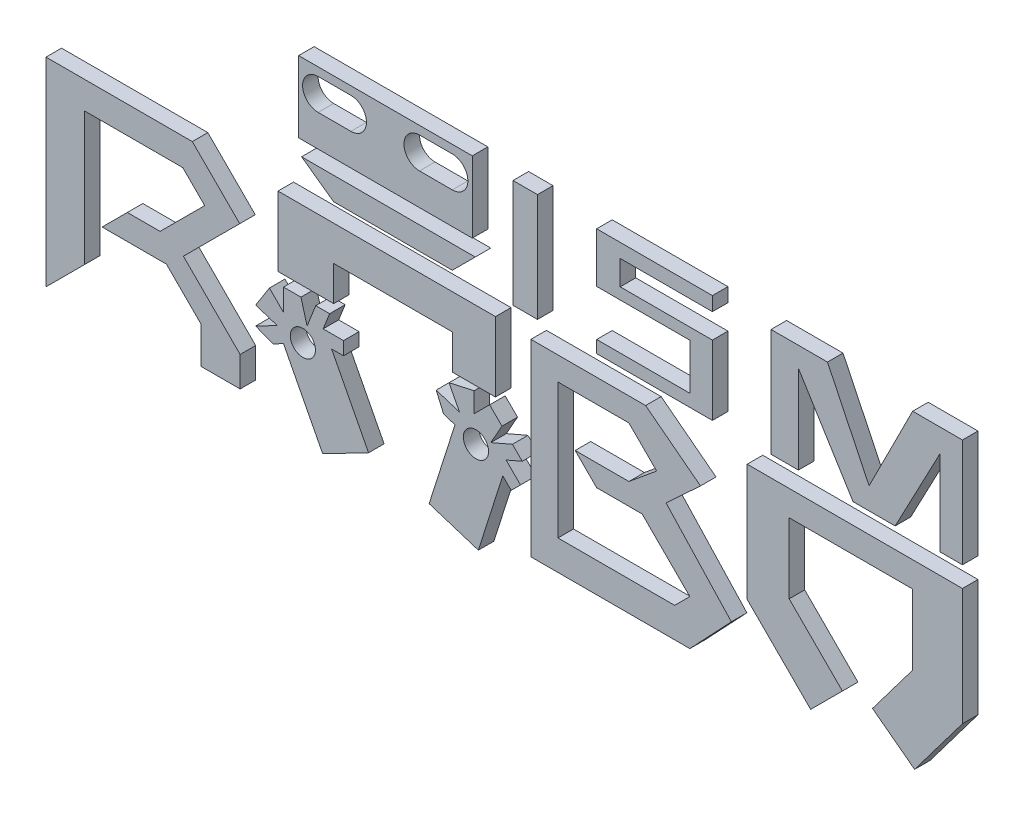
SolidWorks part; units mm, degrees
ref_plane "Front Plane" through (0, 0, 0) normal (0, 0, 1) x (1, 0, 0)
ref_plane "Top Plane" through (0, 0, 0) normal (0, 1, 0) x (1, 0, 0)
ref_plane "Right Plane" through (0, 0, 0) normal (1, 0, 0) x (0, 0, -1)
sketch "Sketch1" plane through (0, 0, 0) normal (0, 0, 1) x (1, 0, 0)
  line L0 (-187.765, 24.8798) -> (-187.765, -40.178)
  line L1 (-187.765, -40.178) -> (-175.1759, -27.5889)
  line L2 (-175.1759, -27.5889) -> (-175.1759, 15.9373)
  line L3 (-175.1759, 15.9373) -> (-143.0335, 15.9373)
  line L4 (-187.765, 24.8798) -> (-139.9227, 24.8798)
  line L5 (-139.9227, 24.8798) -> (-124.4177, 9.3749)
  line L6 (-143.0335, 15.9373) -> (-135.8684, 8.7722)
  line L7 (-135.8684, 8.7722) -> (-150.4664, -5.8258)
  line L8 (-150.4664, -5.8258) -> (-161.1806, -5.8258)
  line L9 (-161.1806, -5.8258) -> (-169.417, -14.0623)
  line L10 (-169.417, -14.0623) -> (-148.3906, -14.0623)
  line L11 (-148.3906, -14.0623) -> (-137.1407, -25.3121)
  line L12 (-137.1407, -25.3121) -> (-137.1407, -37.3655)
  line L13 (-124.4177, 9.3749) -> (-142.8326, -9.04)
  line L14 (-142.8326, -9.04) -> (-124.2838, -27.5889)
  line L15 (-124.2838, -27.5889) -> (-124.2838, -37.3655)
  line L16 (-124.2838, -37.3655) -> (-137.1407, -37.3655)
  line L17 (-105.4731, 24.8798) -> (-48.6883, 24.8798)
  line L18 (-105.4731, 24.8798) -> (-111.9016, 24.8798)
  line L33 (-40.7899, 24.8798) -> (-45.3328, 24.8798)
  line L34 (-45.3328, 24.8798) -> (-48.6883, 24.8798)
  line L35 (-29.196, 24.2407) -> (-29.196, -37.3655)
  line L36 (-86.2487, 10.4463) -> (-62.1419, 10.4463)
  line L37 (-86.2487, 10.4463) -> (-86.2487, -10.3123)
  line L38 (-86.2487, -10.3123) -> (-62.1419, -10.3123)
  line L39 (-62.1419, 10.4463) -> (-62.1419, -10.3123)
  line L44 (-29.196, -37.3655) -> (22.7675, -37.3655)
  line L45 (-29.196, 24.2407) -> (8.3034, 24.2407)
  line L46 (8.3034, 24.2407) -> (26.2496, 10.4463)
  line L47 (26.2496, 10.4463) -> (14.9998, 0)
  line L48 (14.9998, 0) -> (36.3407, -22.9825)
  line L49 (22.7675, -37.3655) -> (36.3407, -22.9825)
  line L50 (-111.9016, 24.8798) -> (-111.9016, 2.1001)
  line L51 (-20.3568, 16.5764) -> (2.8429, 16.5764)
  line L52 (2.8429, 16.5764) -> (11.9195, 7.4999)
  line L54 (7.1651, -7.0311) -> (22.7675, -22.6336)
  line L55 (22.7675, -22.6336) -> (17.8122, -27.5889)
  line L57 (-20.3568, -27.5889) -> (-20.3568, 16.5764)
  line L58 (-14.7319, 0) -> (2.8429, 0)
  line L59 (-14.7319, 0) -> (-7.7008, -7.0311)
  line L60 (-7.7008, -7.0311) -> (7.1651, -7.0311)
  line L61 (17.8122, -27.5889) -> (-20.3568, -27.5889)
  line L62 (41.5172, 24.2407) -> (41.5172, -14.0623)
  line L63 (41.5172, -14.0623) -> (62.2758, -34.8209)
  line L64 (72.6551, -24.4416) -> (62.2758, -34.8209)
  line L65 (72.6551, -24.4416) -> (55.2447, -7.0311)
  line L66 (55.2447, -7.0311) -> (55.2447, 15.9373)
  line L67 (55.2447, 15.9373) -> (95.6235, 15.9373)
  line L68 (95.6235, 15.9373) -> (95.6235, -7.0311)
  line L69 (95.6235, -7.0311) -> (82.4987, -24.4416)
  line L70 (82.4987, -24.4416) -> (96.2672, -34.8209)
  line L71 (96.2672, -34.8209) -> (111.916, -14.0623)
  line L72 (111.916, -14.0623) -> (111.916, 24.2407)
  line L73 (111.916, 24.2407) -> (41.5172, 24.2407)
  line L74 (-93.695, 30.937) -> (-54.9099, 30.937)
  line L75 (-54.9099, 30.937) -> (-47.41, 38.4369)
  line L76 (-47.41, 38.4369) -> (-104.1948, 38.4369)
  line L77 (-104.1948, 38.4369) -> (-93.695, 30.937)
  line L78 (-98.7817, 58.7937) -> (-88.0676, 58.7937) construction
  line L79 (-105.1597, 43.312) -> (-48.3748, 43.312)
  line L80 (-105.1597, 43.312) -> (-105.1597, 66.6152)
  line L81 (-105.1597, 66.6152) -> (-48.3748, 66.6152)
  line L82 (-48.3748, 43.312) -> (-48.3748, 66.6152)
  line L85 (-65.624, 58.7937) -> (-54.9099, 58.7937) construction
  line L86 (-65.624, 63.8829) -> (-54.9099, 63.8829)
  line L87 (-65.624, 53.7045) -> (-54.9099, 53.7045)
  line L88 (104.6063, 30.937) -> (111.916, 30.937)
  line L91 (-63.8829, 59.0616) -> (-57.1866, 59.0616) construction
  line L92 (-63.8829, 61.7401) -> (-57.1866, 61.7401)
  line L93 (-63.8829, 56.3831) -> (-57.1866, 56.3831)
  line L94 (111.916, 30.937) -> (111.916, 66.2936)
  line L95 (111.916, 66.2936) -> (104.6063, 66.2936)
  line L96 (104.6063, 66.2936) -> (95.6235, 66.2936)
  line L97 (104.6063, 30.937) -> (104.6063, 58.7937)
  line L98 (104.6063, 58.7937) -> (89.9058, 30.937)
  line L99 (89.9058, 30.937) -> (76.1379, 30.937)
  line L100 (76.1379, 30.937) -> (58.2678, 59.7833)
  line L101 (58.2678, 59.7833) -> (58.2678, 30.937)
  line L102 (58.2678, 30.937) -> (49.3197, 30.937)
  line L103 (49.3197, 30.937) -> (49.3197, 66.2936)
  line L104 (49.3197, 66.2936) -> (67.7728, 66.2936)
  line L105 (67.7728, 66.2936) -> (81.3854, 38.0643)
  line L106 (81.3854, 38.0643) -> (95.6235, 66.2936)
  line L107 (-35.0483, 66.2936) -> (-35.0483, 30.937)
  line L108 (-35.0483, 30.937) -> (-27.0589, 30.937)
  line L109 (-27.0589, 30.937) -> (-27.0589, 66.2936)
  line L110 (-27.0589, 66.2936) -> (-35.0483, 66.2936)
  line L111 (30.1451, 66.2936) -> (-7.7008, 66.2936)
  line L112 (-7.7008, 49.9688) -> (-7.7008, 66.2936)
  line L113 (-7.7008, 49.9688) -> (22.7675, 49.9688)
  line L114 (22.7675, 49.9688) -> (22.7675, 34.9488)
  line L115 (22.7675, 34.9488) -> (-7.7008, 34.9488)
  line L116 (-7.7008, 34.9488) -> (-7.7008, 30.937)
  line L117 (-7.7008, 30.937) -> (30.1451, 30.937)
  line L118 (30.1451, 30.937) -> (30.1451, 53.7045)
  line L119 (30.1451, 53.7045) -> (0, 53.7045)
  line L120 (30.1451, 66.2936) -> (30.1451, 61.7401)
  line L121 (30.1451, 61.7401) -> (0, 61.7401)
  line L122 (0, 61.7401) -> (0, 53.7045)
  line L147 (-98.7817, 63.8829) -> (-88.0676, 63.8829)
  line L150 (-98.7817, 53.7045) -> (-88.0676, 53.7045)
  line L151 (-97.0407, 59.0616) -> (-90.3444, 59.0616) construction
  line L152 (-97.0407, 61.7401) -> (-90.3444, 61.7401)
  line L153 (-97.0407, 56.3831) -> (-90.3444, 56.3831)
  line L154 (-111.9016, 2.1001) -> (-93.695, 2.1001)
  line L155 (11.9195, 7.4999) -> (2.8429, 0)
  line L156 (-93.695, 2.1001) -> (-93.695, 13.49)
  line L157 (-93.695, 13.49) -> (-54.9099, 13.49)
  line L158 (-54.9099, 13.49) -> (-54.9099, 2.1001)
  line L159 (-54.9099, 2.1001) -> (-40.7899, 2.1001)
  line L160 (-40.7899, 2.1001) -> (-40.7899, 24.8798)
  line L161 (-37.3089, -13.9973) -> (-32.6029, -18.7034)
  line L162 (-38.6583, -5.0798) -> (-42.3284, -11.5723)
  line L163 (-57.7515, -11.1973) -> (-54.0286, -12.3819)
  line L164 (-47.7737, 0.3894) -> (-47.7737, -6.127)
  line L165 (-62.4816, -38.9483) -> (-48.8511, -43.2853)
  line L166 (-38.4086, -19.0026) -> (-46.3846, -44.0701)
  line L167 (-52.5593, -8.0423) -> (-60.1659, -5.622)
  line L168 (-35.2369, -8.5013) -> (-32.0279, -11.7103)
  line L169 (-46.3846, -44.0701) -> (-48.8511, -43.2853)
  line L170 (-32.0279, -11.7103) -> (-37.3089, -13.9973)
  line L171 (-42.6924, -1.0457) -> (-38.6583, -5.0798)
  line L172 (-55.9775, -1.4337) -> (-47.7737, 0.3894)
  line L173 (-60.1659, -5.622) -> (-57.7515, -11.1973)
  line L174 (-55.9775, -1.4337) -> (-52.5593, -8.0423)
  line L175 (-38.4086, -19.0026) -> (-35.6554, -21.7559)
  line L176 (-47.7737, -6.127) -> (-42.6924, -1.0457)
  line L177 (-32.6029, -18.7034) -> (-35.6554, -21.7559)
  line L184 (-54.0286, -12.3819) -> (-62.4816, -38.9483)
  line L185 (-35.2369, -8.5013) -> (-42.3284, -11.5723)
  line L188 (-114.7057, -3.9857) -> (-110.0979, -8.5934)
  line L189 (-110.0979, -8.5934) -> (-110.0979, -1.4075)
  line L190 (-119.2175, -11.0757) -> (-112.1275, -13.3317)
  line L191 (-112.1275, -13.3317) -> (-119.2175, -16.999)
  line L192 (-104.3928, -1.4075) -> (-102.3971, -8.5934)
  line L193 (-94.3714, -11.0757) -> (-82.2859, -34.441)
  line L194 (-99.5542, -1.4075) -> (-102.3971, -8.5934)
  line L195 (-94.3714, -11.0757) -> (-90.4777, -11.0757)
  line L196 (-95.0159, -1.4075) -> (-97.1331, -6.7589)
  line L197 (-97.1331, -6.7589) -> (-90.4777, -6.7589)
  line L198 (-119.2175, -11.0757) -> (-114.7057, -3.9857)
  line L199 (-110.0979, -1.4075) -> (-104.3928, -1.4075)
  line L200 (-99.5542, -1.4075) -> (-95.0159, -1.4075)
  line L201 (-90.4777, -6.7589) -> (-90.4777, -11.0757)
  line L202 (-119.2175, -16.999) -> (-113.568, -19.2341)
  line L203 (-113.568, -19.2341) -> (-110.0979, -17.4392)
  line L204 (-110.0979, -17.4392) -> (-97.2897, -42.2016)
  line L205 (-97.2897, -42.2016) -> (-84.8908, -35.7884)
  line L206 (-82.2859, -34.441) -> (-84.8908, -35.7884)
  arc A2 (-65.624, 63.8829) -> (-65.624, 53.7045) centre (-65.624, 58.7937) ccw
  arc A3 (-54.9099, 53.7045) -> (-54.9099, 63.8829) centre (-54.9099, 58.7937) ccw
  arc A6 (-63.8829, 61.7401) -> (-63.8829, 56.3831) centre (-63.8829, 59.0616) ccw
  arc A7 (-57.1866, 56.3831) -> (-57.1866, 61.7401) centre (-57.1866, 59.0616) ccw
  arc A17 (-98.7817, 63.8829) -> (-98.7817, 53.7045) centre (-98.7817, 58.7937) ccw
  arc A18 (-88.0676, 53.7045) -> (-88.0676, 63.8829) centre (-88.0676, 58.7937) ccw
  arc A19 (-97.0407, 61.7401) -> (-97.0407, 56.3831) centre (-97.0407, 59.0616) ccw
  arc A20 (-90.3444, 56.3831) -> (-90.3444, 61.7401) centre (-90.3444, 59.0616) ccw
  circle A21 centre (-103.7742, -14.0549) radius 4.1237
  circle A22 centre (-47.164, -14.4603) radius 4.1237
  point P31 (-93.4247, 58.7937)
  point P86 (-93.6925, 59.0616)
  point P87 (-60.2669, 58.7937)
  point P101 (-60.5348, 59.0616)
  point P149 (0, 0)
  point P158 (0, 0)
  point P172 (0, 0)
  point P173 (0, 0)
  point P174 (0, 0)
  point P175 (0, 0)
  point P176 (0, 0)
  point P177 (0, 0)
  point P178 (0, 0)
  point P179 (0, 0)
extrude "Boss-Extrude2" add sketch "Sketch1" along normal blind 5.08 contours L159 L160 L33 L34 L17 L18 L50 L154 L156 L157 L158 | L206 L193 L195 L201 L197 L196 L200 L194 L192 L199 L189 L188 L198 L190 L191 L202 L203 L204 L205 A21 | L168 L185 L162 L171 L176 L164 L172 L174 L167 L173 L163 L184 L165 L169 L166 L175 L177 L161 L170 A22 | L106 L105 L104 L103 L102 L101 L100 L99 L98 L97 L88 L94 L95 L96 | L122 L121 L120 L111 L112 L113 L114 L115 L116 L117 L118 L119 | L76 L77 L74 L75 | L16 L15 L14 L13 L5 L4 L0 L1 L2 L3 L6 L7 L8 L9 L10 L11 L12 | L72 L73 L62 L63 L64 L65 L66 L67 L68 L69 L70 L71 | L44 L49 L48 L47 L46 L45 L35 L52 L155 L58 L59 L60 L54 L55 L61 L57 L51 | L79 L82 L81 L80 A18 L150 A17 L147 A3 L87 A2 L86 | L107 L108 L109 L110
